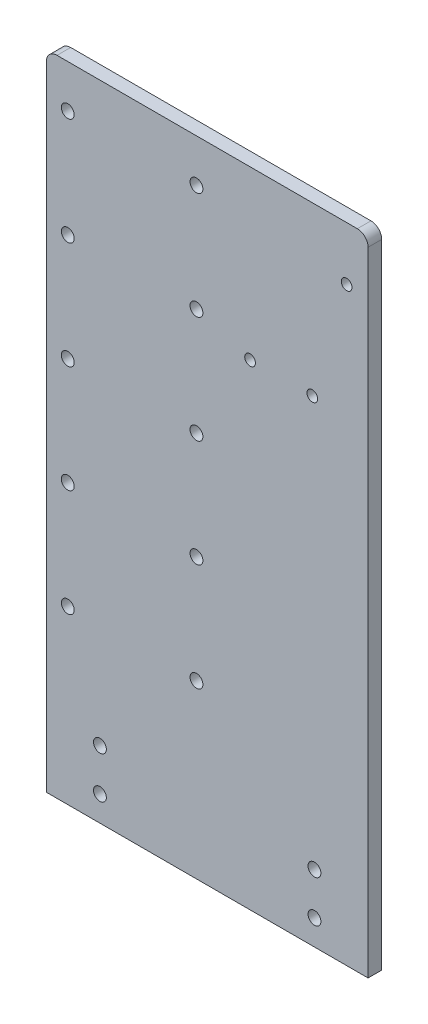
SolidWorks part; units mm, degrees
ref_plane "Front Plane" through (0, 0, 0) normal (0, 0, 1) x (1, 0, 0)
ref_plane "Top Plane" through (0, 0, 0) normal (0, 1, 0) x (1, 0, 0)
ref_plane "Right Plane" through (0, 0, 0) normal (1, 0, 0) x (0, 0, -1)
sketch "Sketch1" plane through (0, 0, 0) normal (0, 0, 1) x (1, 0, 0)
  line L1 (-52.5113, 81.6238) -> (97.4887, 81.6238)
  line L2 (-52.5113, 81.6238) -> (-52.5113, -218.3762)
  line L3 (-52.5113, -218.3762) -> (97.4887, -218.3762)
  line L4 (97.4887, 81.6238) -> (97.4887, -218.3762)
  dimension "D1" = 150
  dimension "D2" = 300
extrude "Boss-Extrude1" add sketch "Sketch1" along normal blind 6.35
sketch "Sketch2" plane through (0, 0, 6.35) normal (0, 0, 1) x (1, 0, 0)
  line L0 (-52.5113, -218.3762) -> (97.4887, -218.3762) construction
  line L1 (22.4887, 81.6238) -> (22.4887, -218.3762) construction
  line L2 (97.4887, 81.6238) -> (-52.5113, 81.6238) construction
  circle A0 centre (-27.5113, -206.5762) radius 3
  circle A1 centre (-27.5113, -187.0762) radius 3
  circle A2 centre (72.4887, -206.5762) radius 3
  circle A3 centre (72.4887, -187.0762) radius 3
  dimension "D1" = 6
  dimension "D2" = 19.5
  dimension "D3" = 31.3
  dimension "D4" = 100
extrude "Cut-Extrude1" cut sketch "Sketch2" against normal through all
sketch "Sketch3" plane through (0, 0, 6.35) normal (0, 0, 1) x (1, 0, 0)
  line L0 (97.4887, 81.6238) -> (-52.5113, 81.6238) construction
  line L1 (97.4887, -218.3762) -> (97.4887, 81.6238) construction
  line L2 (-52.5113, -218.3762) -> (97.4887, -218.3762) construction
  line L3 (-52.5113, 81.6238) -> (-52.5113, -218.3762) construction
  circle A0 centre (42.4887, 3.6238) radius 2.5
  circle A1 centre (71.4887, 3.6238) radius 2.5
  circle A2 centre (87.4887, 56.6238) radius 2.5
  circle A3 centre (-42.5113, -38.3762) radius 3
  circle A4 centre (17.4887, -38.3762) radius 3
  circle A5 centre (-42.5113, -138.3762) radius 3
  circle A6 centre (17.4887, -138.3762) radius 3
  circle A7 centre (-42.5113, -88.3762) radius 3
  circle A8 centre (17.4887, -88.3762) radius 3
  circle A9 centre (-42.5113, 11.6238) radius 3
  circle A10 centre (17.4887, 11.6238) radius 3
  circle A11 centre (-42.5113, 61.6238) radius 3
  circle A12 centre (17.4887, 61.6238) radius 3
  dimension "D1" = 5
  dimension "D14" = 6
  dimension "D2" = 29
  dimension "D3" = 16
  dimension "D4" = 53
  dimension "D5" = 25
  dimension "D6" = 10
  dimension "D7" = 60
  dimension "D8" = 50
  dimension "D9" = 50
  dimension "D10" = 80
  dimension "D11" = 50
  dimension "D12" = 50
  dimension "D13" = 10
extrude "Cut-Extrude2" cut sketch "Sketch3" against normal through all
fillet "Fillet1" radius 5 2 edges at (97.4887, 81.6238, 3.175) (-52.5113, 81.6238, 3.175)
